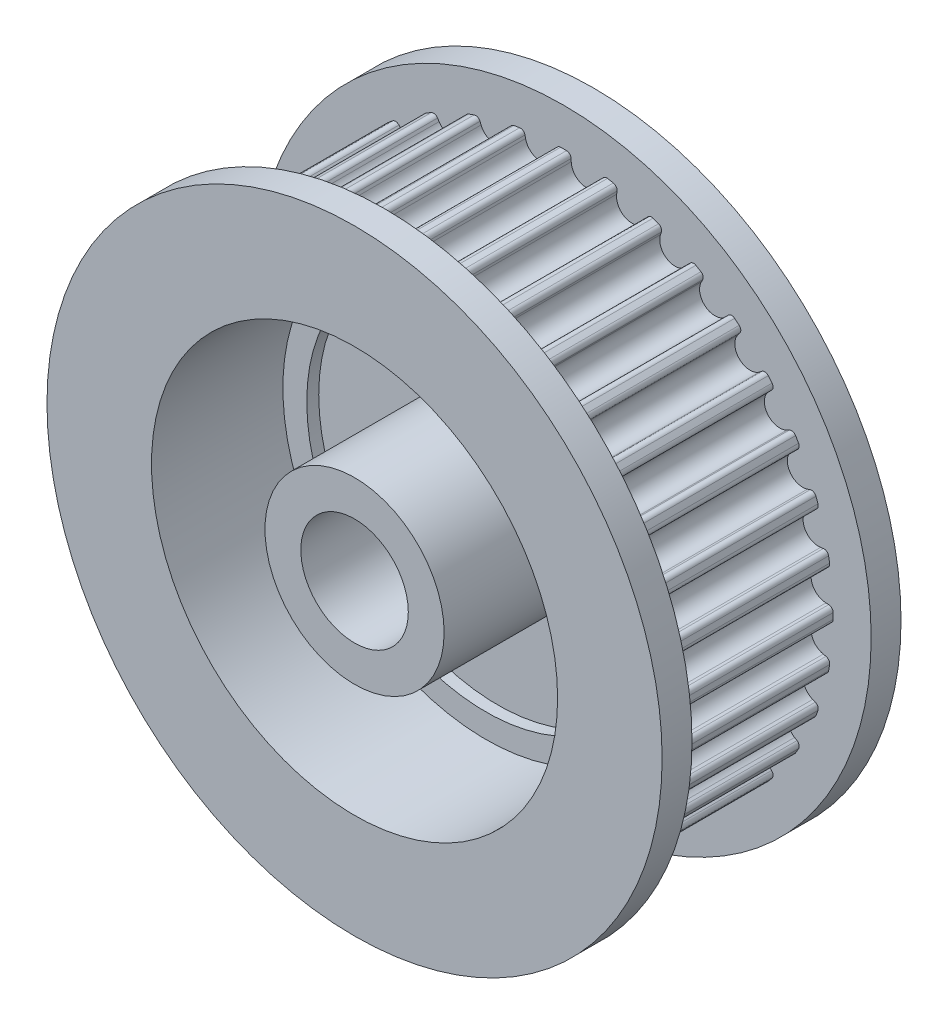
SolidWorks part; units mm, degrees
ref_plane "前视基准面" through (0, 0, 0) normal (0, 0, 1) x (1, 0, 0)
ref_plane "上视基准面" through (0, 0, 0) normal (0, 1, 0) x (1, 0, 0)
ref_plane "右视基准面" through (0, 0, 0) normal (1, 0, 0) x (0, 0, -1)
sketch "Sketch2" plane through (0, 0, 0) normal (0, 0, 1) x (1, 0, 0)
  circle A0 centre (0, 0) radius 45.15
  dimension "D1" = 90.3
extrude "Extrude1" add sketch "Sketch2" along normal mid plane 30
sketch "Sketch1" plane through (0, 0, 15) normal (0, 0, 1) x (1, 0, 0)
  line L0 (0, 0) -> (0, 45.835) construction
  line L1 (0, 0) -> (-3.9948, 45.6606) construction
  line L2 (-1.2656, 44.3946) -> (-1.2821, 43.9222)
  line L3 (-6.4627, 43.9399) -> (-6.3644, 43.4775)
  circle A0 centre (0, 0) radius 45.835 construction
  arc A1 (-0.4946, 45.1473) -> (-7.3526, 44.5473) centre (0, 0) ccw
  arc A2 (-6.3644, 43.4775) -> (-1.2821, 43.9222) centre (-3.8505, 44.0119) ccw
  arc A3 (-0.4946, 45.1473) -> (-1.2656, 44.3946) centre (-0.4861, 44.3673) ccw
  arc A4 (-7.3526, 44.5473) -> (-6.4627, 43.9399) centre (-7.2256, 43.7777) cw
  point P4 (45.6606, 3.9948)
  point P5 (44.2732, 11.863)
  point P6 (41.5406, 19.3707)
  point P7 (37.5458, 26.2899)
  point P8 (32.4102, 32.4102)
  point P9 (26.2899, 37.5458)
  point P10 (19.3707, 41.5406)
  point P11 (11.863, 44.2732)
  point P12 (3.9948, 45.6606)
  point P13 (-3.9948, 45.6606)
  point P14 (-11.863, 44.2732)
  point P15 (-19.3707, 41.5406)
  point P16 (-26.2899, 37.5458)
  point P17 (-32.4102, 32.4102)
  point P18 (-37.5458, 26.2899)
  point P19 (-41.5406, 19.3707)
  point P20 (-44.2732, 11.863)
  point P21 (-45.6606, 3.9948)
  point P22 (-45.6606, -3.9948)
  point P23 (-44.2732, -11.863)
  point P24 (-41.5406, -19.3707)
  point P25 (-37.5458, -26.2899)
  point P26 (-32.4102, -32.4102)
  point P27 (-26.2899, -37.5458)
  point P28 (-19.3707, -41.5406)
  point P29 (-11.863, -44.2732)
  point P30 (-3.9948, -45.6606)
  point P31 (3.9948, -45.6606)
  point P32 (11.863, -44.2732)
  point P33 (19.3707, -41.5406)
  point P34 (26.2899, -37.5458)
  point P35 (32.4102, -32.4102)
  point P36 (37.5458, -26.2899)
  point P37 (41.5406, -19.3707)
  point P38 (44.2732, -11.863)
  point P39 (45.6606, -3.9948)
  dimension "D1" = 91.67
  dimension "D2" = 90.3
  dimension "D3" = 5.14
  dimension "D4" = 3.54
  dimension "D5" = 1.56
  dimension "D6" = 7
extrude "Extrude2" cut sketch "Sketch1" against normal through all
pattern_circular "CirPattern1" count 36 over 360 about axis through (0, 0, 0) along (0, 0, 1) of "Extrude2"
sketch "Sketch3" plane through (0, 0, -15) normal (0, 0, -1) x (-1, 0, 0)
  circle A0 centre (0, 0) radius 51.5
  dimension "D1" = 103
extrude "Extrude3" add sketch "Sketch3" along normal blind 5
sketch "Sketch4" plane through (0, 0, 15) normal (0, 0, 1) x (1, 0, 0)
  circle A0 centre (0, 0) radius 51.5
  circle A1 centre (0, 0) radius 51.5 construction
extrude "Extrude4" add sketch "Sketch4" along normal blind 5
sketch "Sketch7" plane through (0, 0, 20) normal (0, 0, 1) x (1, 0, 0)
  circle A0 centre (0, 0) radius 15
  circle A1 centre (0, 0) radius 34
  dimension "D1" = 30
  dimension "D2" = 68
extrude "Extrude7" cut sketch "Sketch7" against normal blind 22
sketch "Sketch8" plane through (0, 0, 20) normal (0, 0, 1) x (1, 0, 0)
  circle A0 centre (0, 0) radius 9
  dimension "D1" = 18
extrude "Extrude8" cut sketch "Sketch8" against normal through all
sketch "Sketch9" plane through (0, 0, -2) normal (0, 0, 1) x (1, 0, 0)
  circle A0 centre (0, 0) radius 30
  circle A1 centre (0, 0) radius 15 construction
  circle A2 centre (0, 0) radius 15
  dimension "D1" = 60
extrude "Extrude9" cut sketch "Sketch9" against normal blind 2
